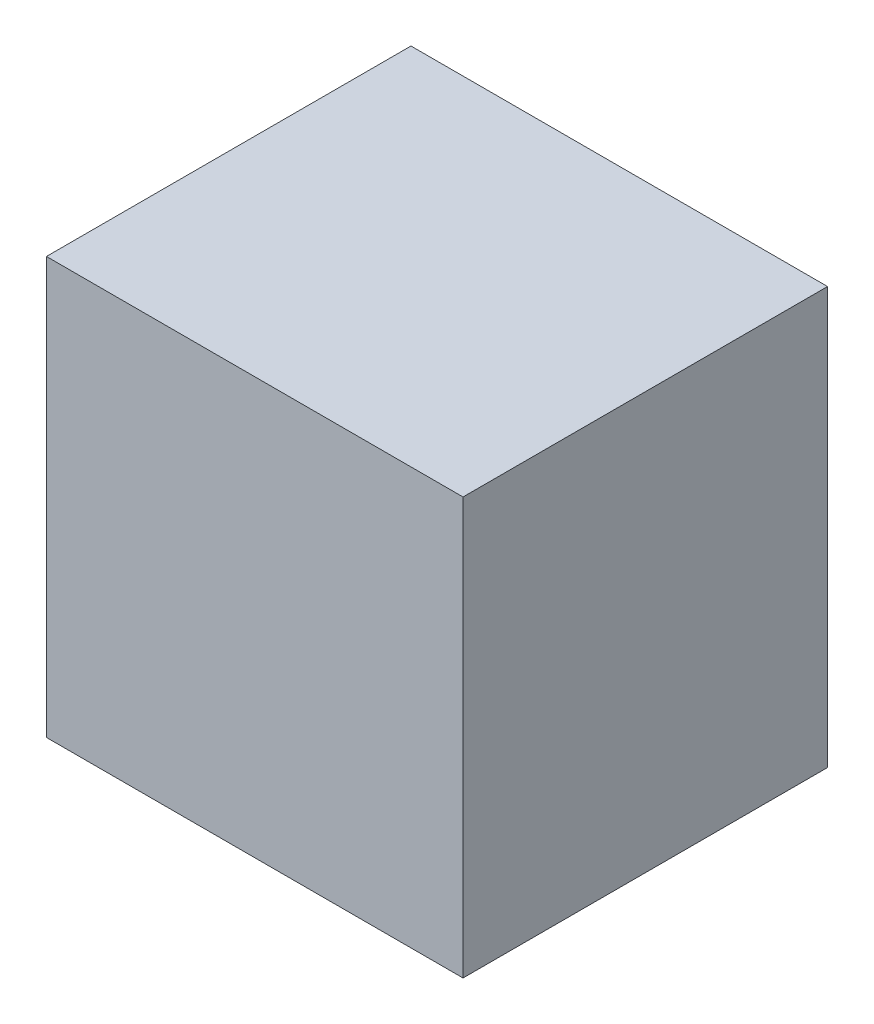
SolidWorks part; units mm, degrees
ref_plane "Front Plane" through (0, 0, 0) normal (0, 0, 1) x (1, 0, 0)
ref_plane "Top Plane" through (0, 0, 0) normal (0, 1, 0) x (1, 0, 0)
ref_plane "Right Plane" through (0, 0, 0) normal (1, 0, 0) x (0, 0, -1)
sketch "Sketch1" plane through (0, 0, 0) normal (0, 0, 1) x (1, 0, 0)
  line L1 (125, -60) -> (-125, -60)
  line L2 (125, -60) -> (125, 60)
  line L3 (125, 60) -> (-125, 60)
  line L4 (-125, -60) -> (-125, 60)
  line L5 (125, -60) -> (-125, 60) construction
  line L6 (125, 60) -> (-125, -60) construction
  point P0 (0, 0)
  dimension "D1" = 250
  dimension "D2" = 120
ref_plane "Plane1" through (0, 0, -10) normal (0, 0, -1) x (-1, 0, 0)
sketch "Sketch2" plane through (0, 0, -10) normal (0, 0, -1) x (-1, 0, 0)
  line L0 (-125, 60) -> (125, -60) construction
  line L1 (125, -60) -> (125, 60) construction
  line L2 (125, 60) -> (-125, 60) construction
  line L3 (-125, 60) -> (-125, -60) construction
  line L4 (-125, -60) -> (125, 60) construction
  line L5 (-125, 0) -> (125, 0) construction
  line L6 (0, 60) -> (0, -60) construction
  line L7 (125, -60) -> (-125, -60) construction
sketch "Sketch4" plane through (0, 0, -10) normal (0, 0, -1) x (-1, 0, 0)
  line L0 (-125, -20) -> (-125, 20)
  line L1 (-125, -20) -> (-85, -20)
  line L2 (-125, 20) -> (-85, 20)
  line L3 (-85, -20) -> (-85, 20)
  line L4 (-125, 60) -> (-125, -60) construction
  line L5 (-125, 0) -> (125, 0) construction
  dimension "D1" = 40
  dimension "D2" = 20
  dimension "D3" = 40
extrude "Boss-Extrude2" add sketch "Sketch4" along normal blind 35 separate body
sketch "Sketch5" plane through (0, 0, -45) normal (0, 0, -1) x (-1, 0, 0)
  line L0 (-125, 0) -> (125, 0) construction
  line L1 (-88, -17) -> (-122, -17)
  line L2 (-88, -17) -> (-88, 17)
  line L3 (-88, 17) -> (-122, 17)
  line L4 (-122, -17) -> (-122, 17)
  line L5 (-88, -17) -> (-122, 17) construction
  line L6 (-88, 17) -> (-122, -17) construction
  line L7 (-85, 20) -> (-125, 20) construction
  line L8 (-125, 60) -> (-125, -60) construction
  line L9 (-85, -20) -> (-85, 20) construction
  line L10 (-125, -20) -> (-85, -20) construction
  point P0 (-105, 0)
  dimension "D1" = 3
  dimension "D2" = 3
  dimension "D3" = 3
  dimension "D4" = 3
extrude "Cut-Extrude1" cut sketch "Sketch5" against normal blind 29 from offset 3
